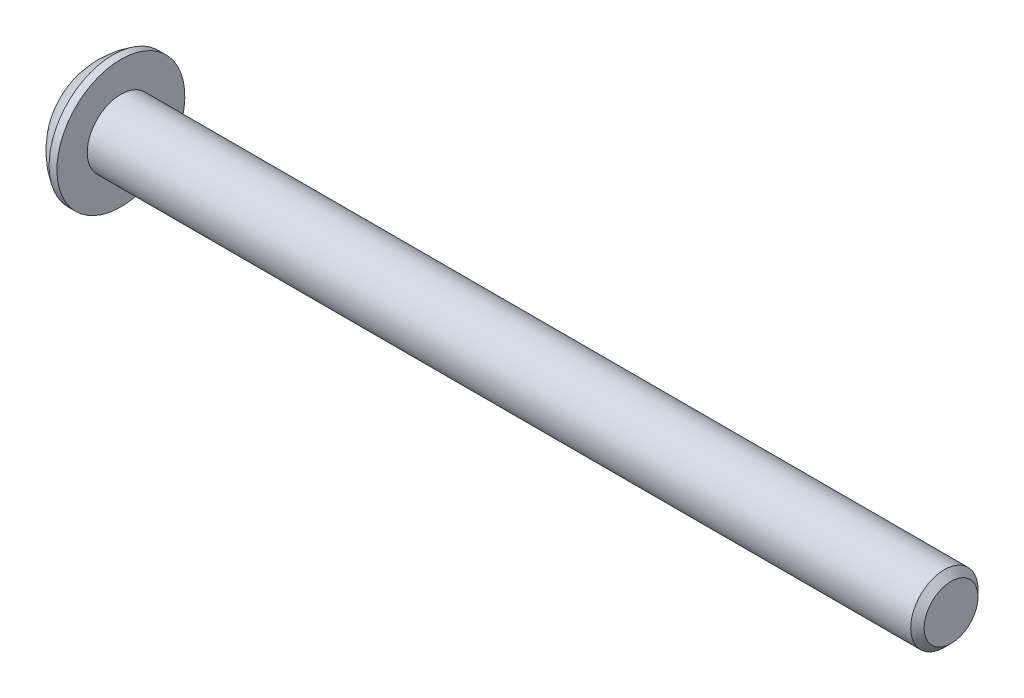
SolidWorks part; units mm, degrees
ref_plane "Front Plane" through (0, 0, 0) normal (0, 0, 1) x (1, 0, 0)
ref_plane "Top Plane" through (0, 0, 0) normal (0, 1, 0) x (1, 0, 0)
ref_plane "Right Plane" through (0, 0, 0) normal (1, 0, 0) x (0, 0, -1)
sketch "Sketch1" plane through (0, 0, 0) normal (0, 0, 1) x (1, 0, 0)
  line L0 (38.65, 0) -> (0, 0)
  line L1 (0, 0) -> (0, 1.425)
  line L2 (1.3, 2.85) -> (1.65, 2.85)
  line L3 (1.65, 2.85) -> (1.65, 1.5)
  line L4 (1.65, 1.5) -> (38.65, 1.5)
  line L5 (38.65, 1.5) -> (38.65, 0)
  arc A1 (0, 1.425) -> (1.3, 2.85) centre (3.0201, -0.0247) cw
  point P6 (0, 0.7125)
  dimension "D5" = 1.65
  dimension "D6" = 2.85
  dimension "D7" = 3.35
  dimension "D1" = 37
  dimension "D2" = 1.5
  dimension "D3" = 1.425
  dimension "D4" = 0.35
revolve "Revolve1" add sketch "Sketch1" angle 360 about L0
sketch "Sketch2" plane through (0, 0, 0) normal (-1, 0, 0) x (0, 0, 1)
  line L1 (1.0093, 0.561) -> (0.0188, 1.1545)
  line L2 (0.0188, 1.1545) -> (-0.9905, 0.5936)
  line L3 (-0.9905, 0.5936) -> (-1.0093, -0.561)
  line L4 (-1.0093, -0.561) -> (-0.0188, -1.1545)
  line L5 (-0.0188, -1.1545) -> (0.9905, -0.5936)
  line L6 (0.9905, -0.5936) -> (1.0093, 0.561)
  circle A0 centre (0, 0) radius 1 construction
  point P1 (-0.9999, 0.0163)
  dimension "D1" = 2
extrude "Cut-Extrude1" cut sketch "Sketch2" against normal blind 1
chamfer "Chamfer1" distance 0.3 angle 45 1 edges at (38.65, 1.5, 0)
